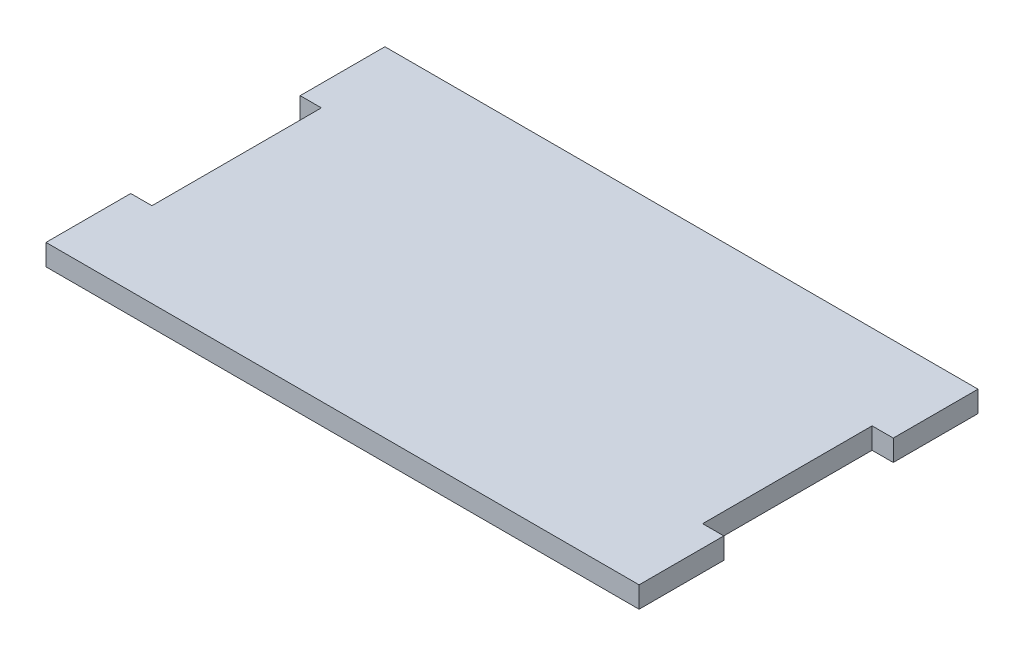
SolidWorks part; units mm, degrees
material "Balsa"
ref_plane "Front Plane" through (0, 0, 0) normal (0, 0, 1) x (1, 0, 0)
ref_plane "Top Plane" through (0, 0, 0) normal (0, 1, 0) x (1, 0, 0)
ref_plane "Right Plane" through (0, 0, 0) normal (1, 0, 0) x (0, 0, -1)
sketch "Sketch1" plane through (0, 0, 0) normal (0, 1, 0) x (1, 0, 0)
  line L0 (-41.275, -12.7) -> (-41.275, 12.7)
  line L1 (-41.275, -25.4) -> (41.275, -25.4)
  line L2 (-41.275, 25.4) -> (41.275, 25.4)
  line L3 (41.275, -12.7) -> (41.275, 12.7)
  line L4 (-41.275, -25.4) -> (41.275, 25.4) construction
  line L5 (-41.275, 25.4) -> (41.275, -25.4) construction
  line L6 (41.275, 25.4) -> (44.45, 25.4)
  line L7 (44.45, 25.4) -> (44.45, 12.7)
  line L8 (44.45, 12.7) -> (41.275, 12.7)
  line L9 (-1.2611, 0) -> (1.2611, 0) construction
  line L10 (0, 25.4) -> (0, -25.4) construction
  line L11 (44.45, -12.7) -> (41.275, -12.7)
  line L12 (44.45, -25.4) -> (44.45, -12.7)
  line L13 (41.275, -25.4) -> (44.45, -25.4)
  line L14 (-41.275, 25.4) -> (-44.45, 25.4)
  line L15 (-44.45, 25.4) -> (-44.45, 12.7)
  line L16 (-44.45, 12.7) -> (-41.275, 12.7)
  line L17 (-44.45, -12.7) -> (-41.275, -12.7)
  line L18 (-41.275, -25.4) -> (-44.45, -25.4)
  line L19 (-44.45, -25.4) -> (-44.45, -12.7)
  point P1 (0, 0)
  point P13 (42.8625, 12.7)
  point P14 (42.8625, -12.7)
  dimension "D1" = 25.4
  dimension "D2" = 12.7
  dimension "D3" = 3.175
  dimension "D4" = 88.9
extrude "Boss-Extrude1" add sketch "Sketch1" along normal blind 3.175
